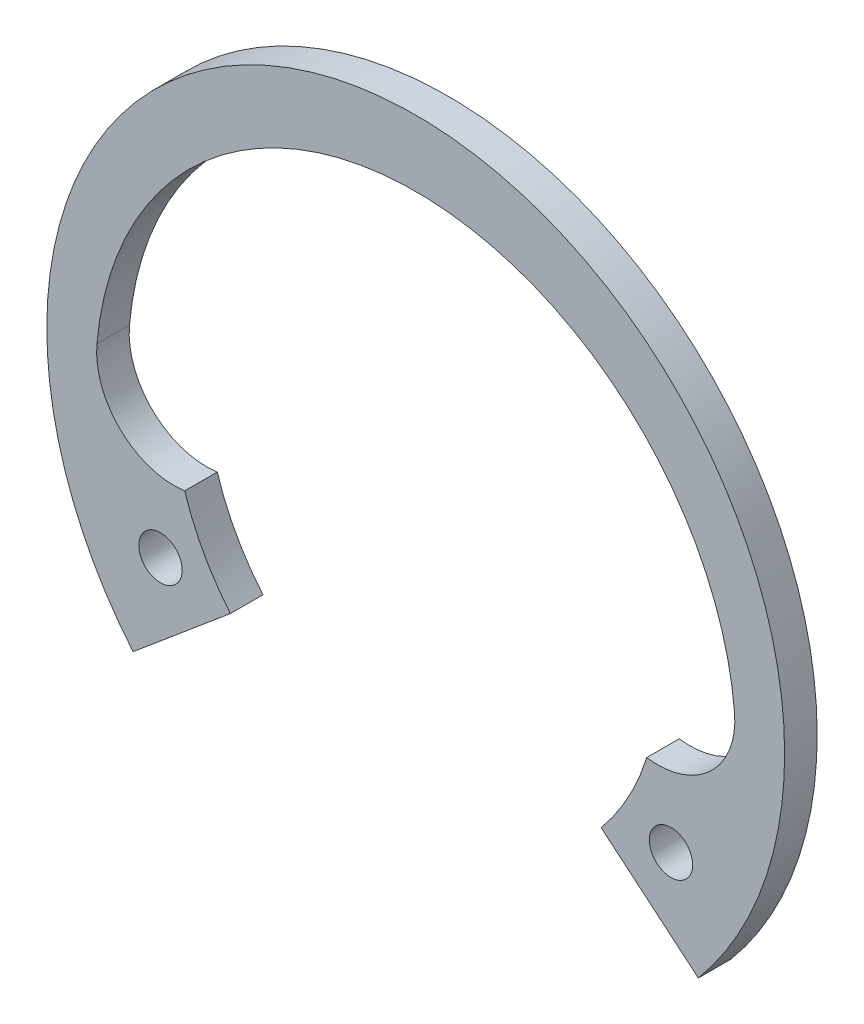
SolidWorks part; units mm, degrees
material "Plain Carbon Steel"
ref_plane "Front Plane" through (0, 0, 0) normal (0, 0, 1) x (1, 0, 0)
ref_plane "Top Plane" through (0, 0, 0) normal (0, 1, 0) x (1, 0, 0)
ref_plane "Right Plane" through (0, 0, 0) normal (1, 0, 0) x (0, 0, -1)
sketch "Sketch1" plane through (0, 0, 0) normal (0, 0, 1) x (1, 0, 0)
  line L0 (0, 17) -> (0, -17) construction
  line L1 (0, 0) -> (13.0228, -10.9274) construction
  line L2 (0, 0) -> (-13.0228, -10.9274) construction
  line L3 (-8.5414, -7.1671) -> (-11.7623, -6.5474) construction
  line L4 (-13.0228, -10.9274) -> (-8.5414, -7.1671)
  line L5 (-11.7623, -6.5474) -> (-13.0228, -10.9274) construction
  line L6 (-11.1482, 0.2014) -> (-8.5414, -7.1671) construction
  line L7 (13.0228, -10.9274) -> (8.5414, -7.1671)
  circle A0 centre (0, 0) radius 17 construction
  circle A1 centre (-11.7623, -6.5474) radius 1
  circle A2 centre (0, 0) radius 11.15 construction
  circle A3 centre (0, -0.8) radius 14.75 construction
  circle A4 centre (-11.1482, 0.2014) radius 3.5569 construction
  arc A5 (-8.5414, -7.1671) -> (-10.6444, -3.3197) centre (0, 0) cw
  arc A6 (-10.6444, -3.3197) -> (-14.6909, 0.5196) centre (-11.1482, 0.2014) cw
  arc A7 (-14.6909, 0.5196) -> (14.6909, 0.5196) centre (0, -0.8) cw
  arc A8 (-13.0228, -10.9274) -> (13.0228, -10.9274) centre (0, 0) cw
  arc A9 (8.5414, -7.1671) -> (10.6444, -3.3197) centre (0, 0) ccw
  circle A10 centre (11.7623, -6.5474) radius 1
  arc A11 (10.6444, -3.3197) -> (14.6909, 0.5196) centre (11.1482, 0.2014) ccw
  dimension "D1" = 34
  dimension "D2" = 100
  dimension "D6" = 2
  dimension "D7" = 0.8
  dimension "D8" = 29.5
  dimension "D3" = 5.85
  dimension "D4" = 3.28
  dimension "D5" = 4.38
  dimension "D9" = 7.816
extrude "Boss-Extrude1" add sketch "Sketch1" along normal blind 1.5
